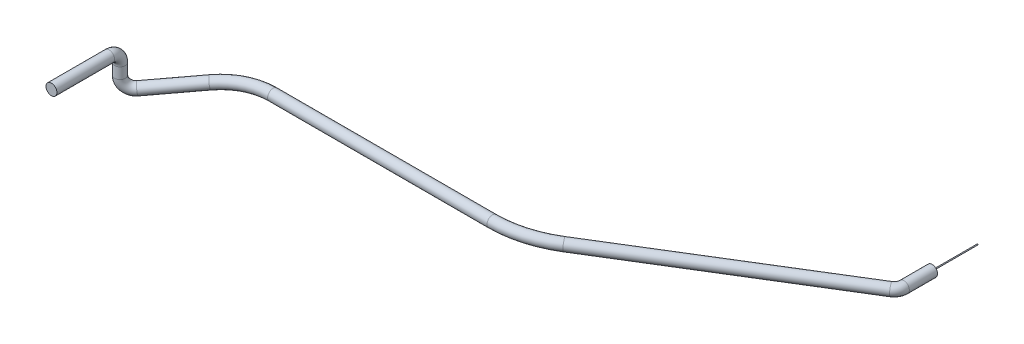
SolidWorks part; units mm, degrees
ref_plane "Front" through (0, 0, 0) normal (0, 0, 1) x (1, 0, 0)
ref_plane "Top" through (0, 0, 0) normal (0, 1, 0) x (1, 0, 0)
ref_plane "Right" through (0, 0, 0) normal (1, 0, 0) x (0, 0, -1)
sketch "Sketch1" plane through (0, 0, 0) normal (0, 0, 1) x (1, 0, 0)
  line L0 (60.65, 12) -> (60.65, 10.7) construction
  line L3 (62.8, -2.15) -> (58.5, -2.15) construction
  circle A0 centre (60.65, -0.65) radius 1.5
  dimension "D1" = 3
sketch3d "3DSketch1"
  line L0 (60.65, -0.65, 0) -> (60.65, -0.65, 7.7521)
  line L1 (59.4242, -0.5605, 10.1736) -> (7.5909, 3.2255, 48.1808)
  line L2 (-7.2397, 3.7086, 53.0308) -> (-67.5752, 3.7086, 53.0308)
  line L3 (-80.2117, 2.6355, 57.7208) -> (-90.8773, 0.5168, 66.9803)
  line L4 (-93.4788, 3.4836, 69.2388) -> (-93.4788, 6.5, 69.2388)
  line L5 (-93.4788, 9.5, 72.2388) -> (-93.4788, 9.5, 88.0913)
  arc A0 (-93.4788, 9.5, 72.2388) -> (-93.4788, 6.5, 69.2388) centre (-93.4788, 6.5, 72.2388) ccw
  arc A1 (-93.4788, 3.4836, 69.2388) -> (-90.8773, 0.5168, 66.9803) centre (-91.2134, 3.4836, 67.2721) ccw
  arc A2 (-7.2397, 3.7086, 53.0308) -> (7.5909, 3.2255, 48.1808) centre (-7.2397, 1.2306, 28.1539) ccw
  arc A3 (-80.2117, 2.6355, 57.7208) -> (-67.5752, 3.7086, 53.0308) centre (-67.5752, -0.5293, 71.5521) ccw
  arc A4 (59.4242, -0.5605, 10.1736) -> (60.65, -0.65, 7.7521) centre (57.658, -0.4315, 7.7521) ccw
  point P10 (-93.4788, 9.5, 69.2388)
  point P11 (-96.4788, 6.5, 72.2388)
  point P14 (-93.4788, 0, 69.2388)
  point P15 (-89.2467, 3.4836, 69.5375)
  point P17 (0.9765, 3.7086, 53.0308)
  point P19 (-7.2397, 26.1075, 25.6759)
  point P22 (-74.8094, 3.7086, 53.0308)
  point P23 (-67.5752, -19.0507, 67.3142)
  point P26 (60.65, -0.65, 9.2748)
  point P27 (57.8765, 2.5606, 7.7521)
  dimension "D1" = 3
  dimension "D2" = 3
  dimension "D3" = 25
  dimension "D4" = 19
  dimension "D5" = 3
  dimension "D6" = 138.312
  dimension "D7" = 9.5
  dimension "D8" = 25
sweep "Base-Sweep" add profiles "Sketch1" path "3DSketch1"
sketch "Sketch2" plane through (0, 0, 0) normal (0, 0, -1) x (-1, 0, 0)
  circle A0 centre (-60.65, -0.65) radius 0.125
  dimension "D1" = 0.25
extrude "Boss-Extrude1" add sketch "Sketch2" along normal blind 12.5
